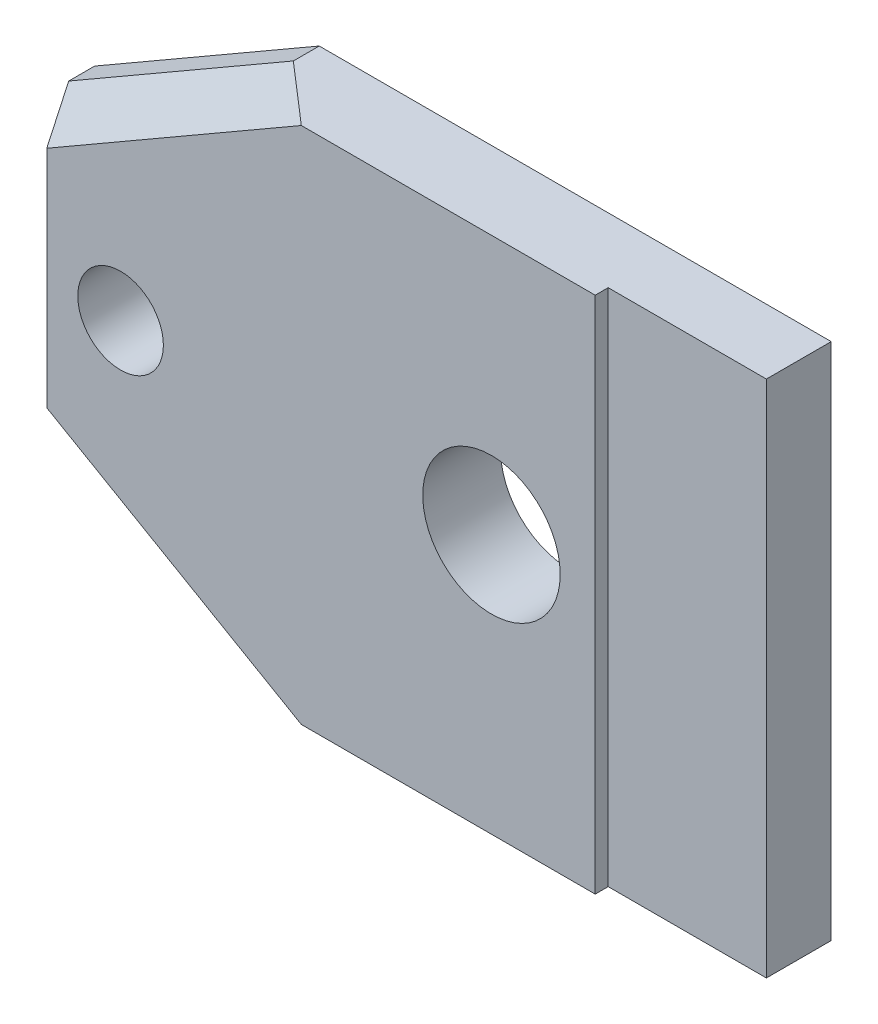
SolidWorks part; units mm, degrees
material "ABS"
ref_plane "Ebene vorne" through (0, 0, 0) normal (0, 0, 1) x (1, 0, 0)
ref_plane "Ebene oben" through (0, 0, 0) normal (0, 1, 0) x (1, 0, 0)
ref_plane "Ebene rechts" through (0, 0, 0) normal (1, 0, 0) x (0, 0, -1)
sketch "Skizze1" plane through (0, 0, 0) normal (0, 0, 1) x (1, 0, 0)
  line L0 (0, 0) -> (28.4, 0)
  line L1 (28.4, 0) -> (28.4, 2.5)
  line L2 (28.4, 2.5) -> (22.3, 2.5)
  line L3 (22.3, 2.5) -> (22.3, 3)
  line L4 (22.3, 3) -> (0, 3)
  line L5 (0, 3) -> (0, 0)
  line L6 (18.3, 3) -> (18.3, 0) construction
  line L7 (4, 3) -> (4, 0) construction
  line L8 (14.3, 3) -> (14.3, 0) construction
  line L9 (14.4, 0) -> (14.4, -6.2) construction
  line L10 (14.4, -6.2) -> (28.4, -6.2) construction
  line L11 (28.4, -6.2) -> (28.4, 0) construction
  line L12 (14.4, -6.2) -> (0, -6.2) construction
  line L13 (0, -6.2) -> (0, 0) construction
  line L14 (4, 0) -> (4, -6.2) construction
  circle A0 centre (4, 3) radius 1.65 construction
  circle A1 centre (18.3, 3) radius 2.65 construction
  dimension "D11" = 3.3
  dimension "D12" = 5.3
  dimension "D1" = 6.1
  dimension "D2" = 3
  dimension "D3" = 2.5
  dimension "D4" = 4
  dimension "D5" = 10.1
  dimension "D6" = 4
  dimension "D7" = 14.3
  dimension "D8" = 28.4
  dimension "D9" = 6.2
  dimension "D10" = 14
extrude "Aufsatz-Linear austragen1" add sketch "Skizze1" along normal blind 20
sketch "Skizze2" plane through (0, 0, 0) normal (0, -1, 0) x (1, 0, 0)
  line L0 (0, 10) -> (28.4, 10) construction
  line L1 (0, 20) -> (0, 0) construction
  line L2 (28.4, 20) -> (28.4, 0) construction
  circle A0 centre (4, 10) radius 1.65
  circle A1 centre (18.3, 10) radius 2.65
  dimension "D3" = 3.3
  dimension "D4" = 5.3
  dimension "D1" = 14.3
  dimension "D2" = 10.1
  dimension "D5" = 4
extrude "Schnitt-Linear austragen1" cut sketch "Skizze2" against normal up to surface (3 mm away) up to face at (11.15, 3, 10)
chamfer "Fase1" distance 5 angle 60 2 edges at (0, 1.5, 0) (0, 1.5, 20)
chamfer "Fase2" distance 2 angle 30 3 edges at (4.3301, 3, 17.5) (4.3301, 3, 2.5) (0, 3, 10)
move or copy body "Körper-Verschieben/Kopieren1" bodies to move or copy 102 copy no rotation origin (0, 1.5, 10) rotation axis (1, 0, 0) rotation angle 90
